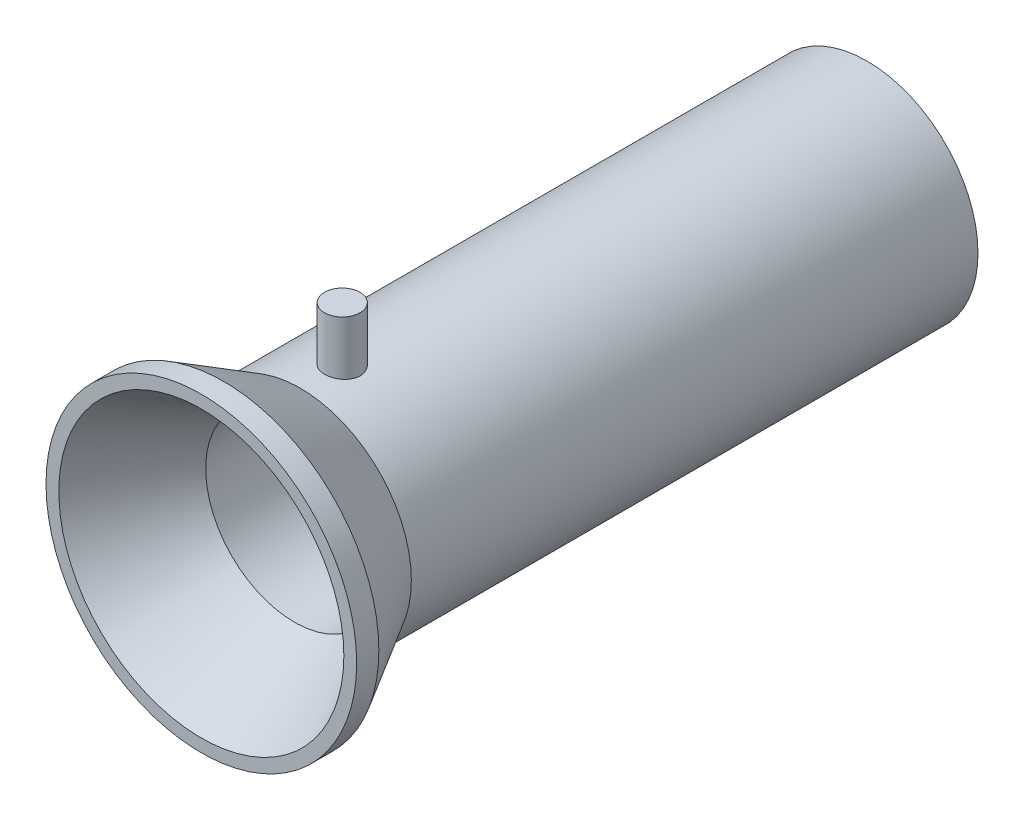
SolidWorks part; units mm, degrees
other "Папка сварных швов"
material "Сталь 12Х18Н9 ГОСТ 5632-72"
ref_plane "Front" through (0, 0, 0) normal (0, 0, 1) x (1, 0, 0)
ref_plane "Top" through (0, 0, 0) normal (0, 1, 0) x (1, 0, 0)
ref_plane "Right" through (0, 0, 0) normal (1, 0, 0) x (0, 0, -1)
sketch "Sketch1" plane through (0, 0, 0) normal (1, 0, 0) x (0, 0, -1)
  line L3 (22.3205, 25) -> (100, 25)
  line L4 (100, 25) -> (100, 20)
  line L6 (0, 32.1132) -> (0, 35)
  line L7 (20.9808, 20) -> (100, 20)
  line L8 (0, 0) -> (8.808, 0) construction
  line L9 (0, 0) -> (0, 6.1121) construction
  line L10 (0, 32.1132) -> (20.9808, 20)
  line L11 (0, 35) -> (5, 35)
  line L13 (22.3205, 25) -> (5, 35)
  point P1 (4.1694, 33.7552)
  point P4 (0, 0)
  point P8 (22.2735, 25)
  point P14 (0, 0)
  point P15 (0, 0)
  dimension "D1" = 50
  dimension "D2" = 5
  dimension "D3" = 15
  dimension "D4" = 30
  dimension "D7" = 5
  dimension "D8" = 5
  dimension "D9" = 100
revolve "Revolve1" add sketch "Sketch1" angle 360 about L8
sketch "Sketch2" plane through (0, 37, 0) normal (0, 1, 0) x (1, 0, 0)
  circle A0 centre (0, 31.7583) radius 4 construction
  circle A1 centre (0, 31.7583) radius 4
extrude "Boss-Extrude1" add sketch "Sketch2" against normal up to body separate body
mirror "Mirror1" about plane through (0, 0, 0) normal (0, 1, 0) of "Boss-Extrude1"
sketch "Sketch3" plane through (0, 0, -100) normal (0, 0, -1) x (-1, 0, 0)
  circle A0 centre (0, 0) radius 25 construction
  circle A1 centre (0, 0) radius 20 construction
  circle A2 centre (0, 0) radius 25
  circle A3 centre (0, 0) radius 20
extrude "Boss-Extrude2" add sketch "Sketch3" along normal blind 50
